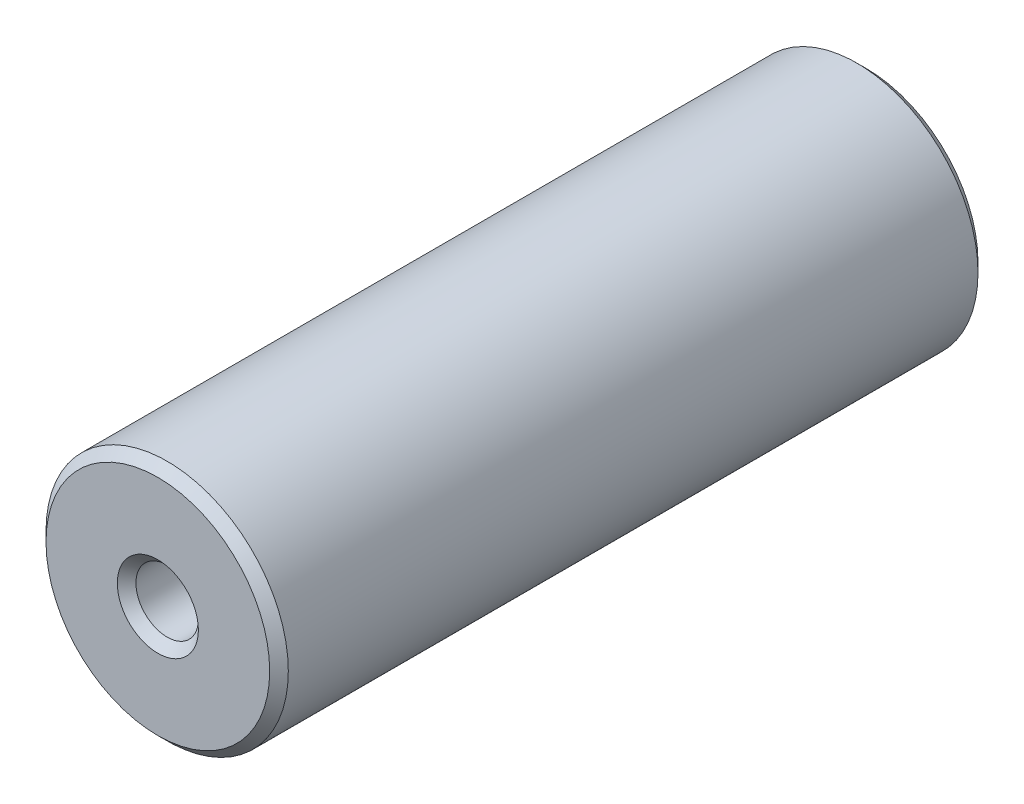
SolidWorks part; units mm, degrees
ref_plane "Plan de face" through (0, 0, 0) normal (0, 0, 1) x (1, 0, 0)
ref_plane "Plan de dessus" through (0, 0, 0) normal (0, 1, 0) x (1, 0, 0)
ref_plane "Plan de droite" through (0, 0, 0) normal (1, 0, 0) x (0, 0, -1)
sketch "Esquisse1" plane through (0, 0, 0) normal (0, 0, 1) x (1, 0, 0)
  circle A0 centre (0, 0) radius 3.35
  circle A1 centre (0, 0) radius 13
  dimension "D2" = 26
extrude "Boss.-Extru.1" add sketch "Esquisse1" along normal blind 76
chamfer "Chanfrein1" distance 1 angle 45 4 edges at (3.35, 0, 0) (3.35, 0, 76) (13, 0, 0) (13, 0, 76)
